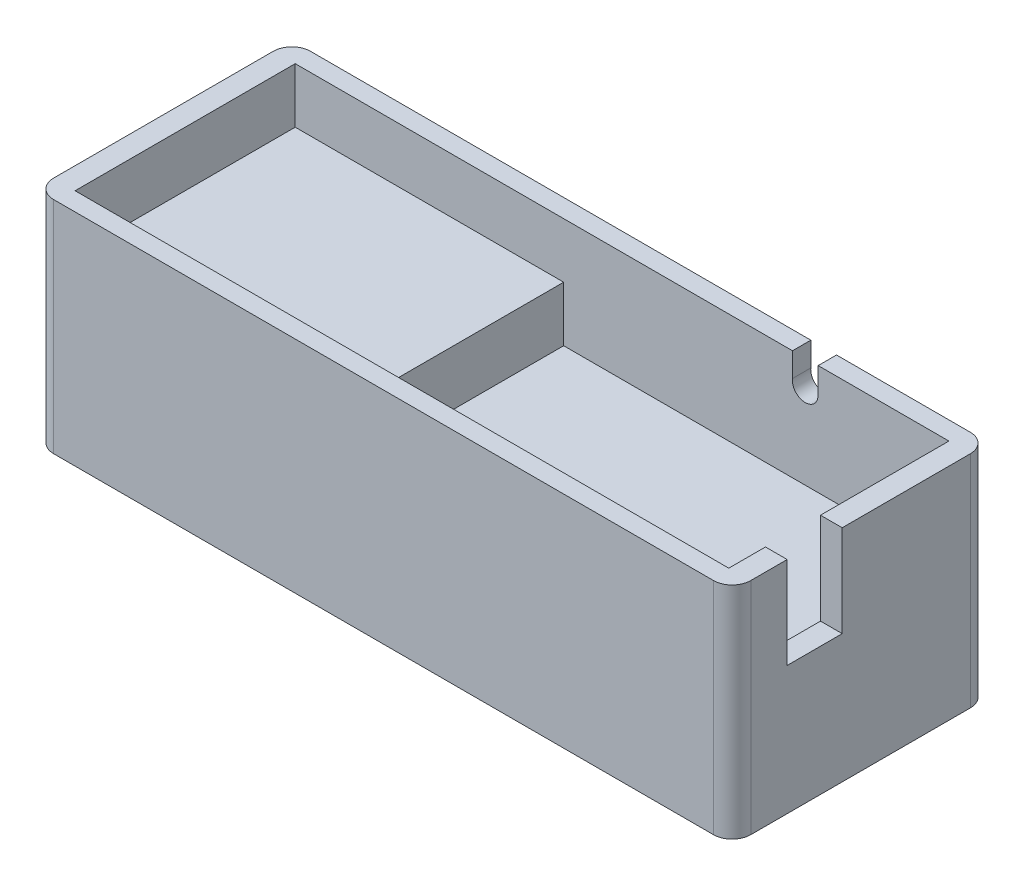
SolidWorks part; units mm, degrees
ref_plane "Front Plane" through (0, 0, 0) normal (0, 0, 1) x (1, 0, 0)
ref_plane "Top Plane" through (0, 0, 0) normal (0, 1, 0) x (1, 0, 0)
ref_plane "Right Plane" through (0, 0, 0) normal (1, 0, 0) x (0, 0, -1)
sketch "Sketch1" plane through (0, 0, 0) normal (0, 1, 0) x (1, 0, 0)
  line L1 (-95, 35) -> (95, 35)
  line L2 (-95, 35) -> (-95, -35)
  line L3 (-95, -35) -> (95, -35)
  line L4 (95, 35) -> (95, -35)
  point P4 (-95, 0)
  point P6 (95, 0)
  point P7 (0, 35)
  point P9 (0, -35)
  dimension "D1" = 95
  dimension "D2" = 95
  dimension "D3" = 35
  dimension "D4" = 35
extrude "Boss-Extrude1" add sketch "Sketch1" along normal blind 60 contours L1 L4 L3 L2
sketch "Sketch2" plane through (0, 60, 0) normal (0, 1, 0) x (1, 0, 0)
  line L1 (-89.0846, -30) -> (89.0846, -30)
  line L2 (-89.0846, -30) -> (-89.0846, 30)
  line L3 (-89.0846, 30) -> (89.0846, 30)
  line L4 (89.0846, -30) -> (89.0846, 30)
  line L5 (-89.0846, -30) -> (89.0846, 30) construction
  line L6 (-89.0846, 30) -> (89.0846, -30) construction
  point P0 (0, 0)
  dimension "D1" = 178.1691
  dimension "D2" = 60
extrude "Cut-Extrude1" cut sketch "Sketch2" against normal blind 50
fillet "Fillet2" radius 5.08 4 edges at (-95, 30, 35) (95, 30, 35) (95, 30, -35) (-95, 30, -35)
sketch "Sketch5" plane through (0, 0, -35) normal (0, 0, -1) x (-1, 0, 0)
  line L0 (-89.92, 60) -> (-89.92, 0) construction
  line L1 (89.92, 60) -> (-89.92, 60) construction
  circle A0 centre (-49.92, 53) radius 3.5
  dimension "D1" = 7
  dimension "D2" = 40
  dimension "D3" = 7
extrude "Cut-Extrude3" cut sketch "Sketch5" against normal blind 11.2109
sketch "Sketch6" plane through (0, 10, 0) normal (0, 1, 0) x (1, 0, 0)
  line L0 (89.0846, 30) -> (-89.0846, 30) construction
  line L1 (89.0846, -30) -> (-90.6121, -30)
  line L2 (89.0846, -30) -> (89.0846, 30)
  line L3 (89.0846, 30) -> (-90.6121, 30)
  line L4 (-90.6121, -30) -> (-90.6121, 30)
  dimension "D1" = 179.6967
extrude "Boss-Extrude3" add sketch "Sketch6" along normal blind 20
sketch "Sketch7" plane through (89.0846, 0, 0) normal (-1, 0, 0) x (0, 0, 1)
  line L0 (30, 30) -> (-30, 30) construction
  line L1 (5, 68.02) -> (20, 68.02)
  line L2 (5, 68.02) -> (5, 35)
  line L3 (5, 35) -> (20, 35)
  line L4 (20, 68.02) -> (20, 35)
  line L5 (-30, 30) -> (-30, 60) construction
  dimension "D1" = 15
  dimension "D2" = 33.02
  dimension "D3" = 5
  dimension "D4" = 35
extrude "Cut-Extrude4" cut sketch "Sketch7" against normal blind 16.51
sketch "Sketch9" plane through (4.7411, 60, 0) normal (0, 1, 0) x (1, 0, 0)
  line L1 (48.7084, 30) -> (41.7084, 30)
  line L2 (48.7084, 30) -> (48.7084, 35)
  line L3 (48.7084, 35) -> (41.7084, 35)
  line L4 (41.7084, 30) -> (41.7084, 35)
  dimension "D1" = 7
extrude "Cut-Extrude5" cut sketch "Sketch9" against normal blind 6.93
sketch "Sketch11" plane through (0, 0, 0) normal (0, -1, 0) x (1, 0, 0)
  line L0 (-89.92, 35) -> (89.92, 35) construction
  line L1 (-82.7485, 29.5) -> (8.2515, 29.5)
  line L2 (-82.7485, 29.5) -> (-82.7485, -29.5)
  line L3 (-82.7485, -29.5) -> (8.2515, -29.5)
  line L4 (8.2515, 29.5) -> (8.2515, -29.5)
  dimension "D1" = 91
  dimension "D2" = 59
  dimension "D3" = 5.5
extrude "Cut-Extrude6" cut sketch "Sketch11" against normal blind 17
sketch "Sketch13" plane through (0, 17, 0) normal (0, -1, 0) x (1, 0, 0)
  line L1 (8.2515, 31.999) -> (-13.0462, 31.999)
  line L2 (8.2515, 31.999) -> (8.2515, 26.284)
  line L3 (8.2515, 26.284) -> (-13.0462, 26.284)
  line L4 (-13.0462, 31.999) -> (-13.0462, 26.284)
  dimension "D1" = 21.2977
extrude "Cut-Extrude7" cut sketch "Sketch13" against normal blind 26.6454
sketch "Sketch14" plane through (0, 30, 0) normal (0, 1, 0) x (1, 0, 0)
  line L0 (-89.0846, -30) -> (89.0846, -30) construction
  line L1 (89.0846, 30) -> (-15.9154, 30)
  line L2 (89.0846, 30) -> (89.0846, -30)
  line L3 (89.0846, -30) -> (-15.9154, -30)
  line L4 (-15.9154, 30) -> (-15.9154, -30)
  dimension "D1" = 105
sketch "Sketch16" plane through (0, 30, 0) normal (0, 1, 0) x (1, 0, 0)
  line L1 (-89.0846, 30) -> (-15.9154, 30)
  line L2 (-89.0846, 30) -> (-89.0846, -30)
  line L3 (-89.0846, -30) -> (-15.9154, -30)
  line L4 (-15.9154, 30) -> (-15.9154, -30)
extrude "Boss-Extrude9" add sketch "Sketch16" along normal blind 15
sketch "Sketch17" plane through (0, 45, 0) normal (0, 1, 0) x (1, 0, 0)
  line L0 (-15.9154, 30) -> (-15.9154, -30) construction
  line L1 (-15.9154, 16.5) -> (-40.9154, 16.5)
  line L2 (-15.9154, 16.5) -> (-15.9154, -16.5)
  line L3 (-15.9154, -16.5) -> (-40.9154, -16.5)
  line L4 (-40.9154, 16.5) -> (-40.9154, -16.5)
  line L5 (-28.4154, 16.5) -> (-28.4154, 30)
  line L6 (46.4495, 30) -> (-89.0846, 30) construction
  line L7 (-28.4154, -16.5) -> (-28.4154, -30)
  line L8 (-89.0846, -30) -> (89.0846, -30) construction
  line L9 (-40.9154, 0) -> (-15.9154, 0)
  circle A0 centre (-28.4154, 0) radius 12.5
  dimension "D1" = 25
  dimension "D2" = 33
sketch "Sketch18" plane through (0, 45, 0) normal (0, 1, 0) x (1, 0, 0)
  line L0 (-40.9154, 0) -> (-89.0846, 0)
  line L1 (-89.0846, 30) -> (-89.0846, -30) construction
  line L3 (-81.5, -16.5) -> (-48.5, -16.5)
  line L4 (-81.5, -16.5) -> (-81.5, 16.5)
  line L5 (-81.5, 16.5) -> (-48.5, 16.5)
  line L6 (-48.5, -16.5) -> (-48.5, 16.5)
  line L7 (-81.5, -16.5) -> (-48.5, 16.5) construction
  line L8 (-81.5, 16.5) -> (-48.5, -16.5) construction
  point P5 (-65, 0)
  dimension "D1" = 33
  dimension "D2" = 33
